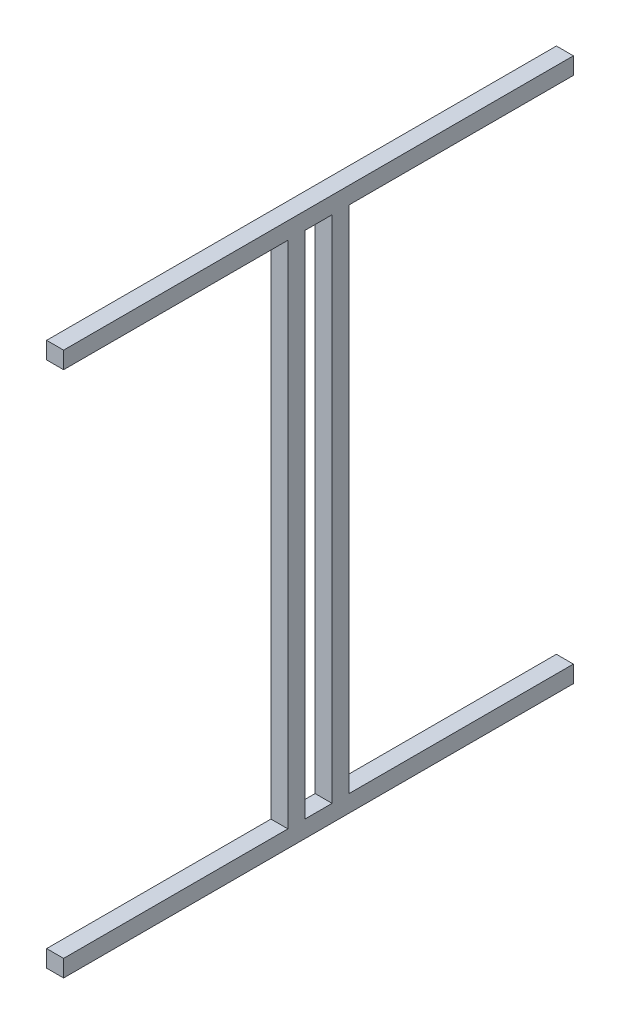
SolidWorks part; units mm, degrees
ref_plane "Front" through (0, 0, 0) normal (0, 0, 1) x (1, 0, 0)
ref_plane "Top" through (0, 0, 0) normal (0, 1, 0) x (1, 0, 0)
ref_plane "Right" through (0, 0, 0) normal (1, 0, 0) x (0, 0, -1)
sketch "Sketch1" plane through (0, 0, 0) normal (1, 0, 0) x (0, 0, -1)
  line L0 (-600, -500) -> (-600, -520)
  line L1 (0, -500) -> (-600, -500)
  line L2 (0, -500) -> (0, -520)
  line L3 (-600, -520) -> (-600, -1120) construction
  line L4 (-600, -1120) -> (-600, -1140)
  line L5 (0, -1120) -> (-600, -1120)
  line L6 (0, -1120) -> (0, -1140)
  line L7 (0, -520) -> (-600, -520)
  line L8 (0, -1140) -> (-600, -1140)
  line L9 (-300, -520) -> (-300, -1120) construction
  line L10 (-300, -1120) -> (-359.4936, -1171.8985) construction
  line L11 (-316, -520) -> (-316, -1120)
  line L12 (20, 0) -> (0, 0)
  line L13 (-600, 0) -> (-620, 0)
  line L14 (20, -1300) -> (0, -1300)
  line L15 (-600, -1300) -> (-620, -1300)
  line L16 (-284, -520) -> (-284, -1120)
  line L17 (-336, -520) -> (-336, -1120)
  line L18 (-264, -520) -> (-264, -1120)
  dimension "D1" = 600
  dimension "D2" = 600
  dimension "D3" = 2
  dimension "D4" = 16
  dimension "D5" = 20
  dimension "D6" = 16
  dimension "D7" = 20
  dimension "D8" = 20
extrude "Boss-Extrude1" add sketch "Sketch1" along normal blind 20
